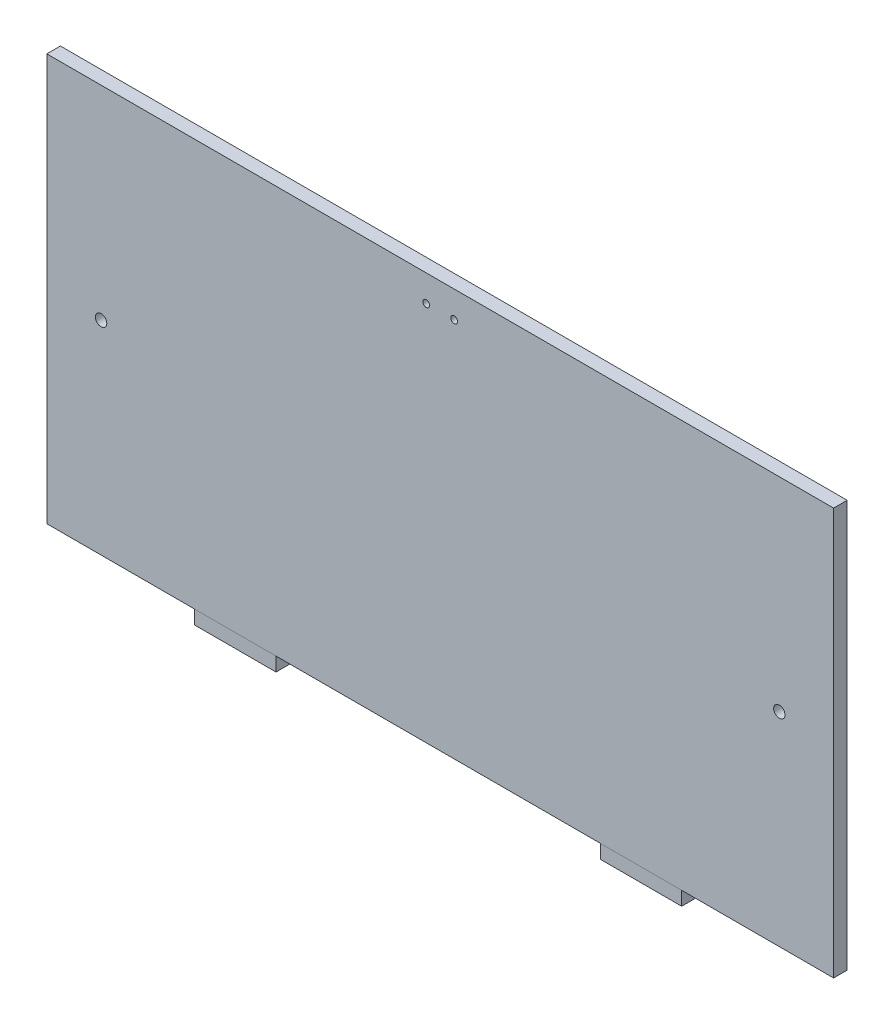
SolidWorks part; units mm, degrees
ref_plane "Front Plane" through (0, 0, 0) normal (0, 0, 1) x (1, 0, 0)
ref_plane "Top Plane" through (0, 0, 0) normal (0, 1, 0) x (1, 0, 0)
ref_plane "Right Plane" through (0, 0, 0) normal (1, 0, 0) x (0, 0, -1)
sketch "Sketch1" plane through (0, 0, 0) normal (0, 0, 1) x (1, 0, 0)
  line L1 (-145, 75) -> (145, 75)
  line L2 (-145, 75) -> (-145, -75)
  line L3 (-145, -75) -> (145, -75)
  line L4 (145, 75) -> (145, -75)
  line L5 (-145, 75) -> (145, -75) construction
  line L6 (-145, -75) -> (145, 75) construction
  point P0 (0, 0)
  dimension "D1" = 290
  dimension "D2" = 150
extrude "Boss-Extrude1" add sketch "Sketch1" along normal blind 5
sketch "Sketch2" plane through (0, 0, 5) normal (0, 0, 1) x (1, 0, 0)
  line L0 (-147.5, 65.2) -> (147.5, 65.2) construction
  line L3 (145, 75) -> (-145, 75) construction
  line L4 (0, 65.2) -> (-5.15, 65.2)
  line L5 (0, 65.2) -> (5.15, 65.2)
  circle A0 centre (-5.15, 65.2) radius 1.25
  circle A1 centre (5.15, 65.2) radius 1.25
  dimension "D2" = 5.15
  dimension "D3" = 2.5
  dimension "D4" = 2.5
  dimension "D1" = 9.8
  dimension "D5" = 5.15
extrude "Cut-Extrude1" cut sketch "Sketch2" against normal blind 5 contours A0 L0 L4 | L0 A0 L4 | L5 L0 A1 | L0 L5 A1
sketch "Sketch3" plane through (0, 0, 5) normal (0, 0, 1) x (1, 0, 0)
  line L0 (0, -75) -> (-145, -75)
  line L2 (-145, -75) -> (145, -75) construction
  line L3 (0, -75) -> (145, -75)
  line L4 (-90.52, -69.9) -> (-60.52, -69.9)
  line L5 (-90.52, -69.9) -> (-90.52, -80.1)
  line L6 (-90.52, -80.1) -> (-60.52, -80.1)
  line L7 (-60.52, -69.9) -> (-60.52, -80.1)
  line L8 (-90.52, -69.9) -> (-60.52, -80.1) construction
  line L9 (-90.52, -80.1) -> (-60.52, -69.9) construction
  line L10 (59, -69.9) -> (89, -69.9)
  line L11 (59, -69.9) -> (59, -80.1)
  line L12 (59, -80.1) -> (89, -80.1)
  line L13 (89, -69.9) -> (89, -80.1)
  line L14 (59, -69.9) -> (89, -80.1) construction
  line L15 (59, -80.1) -> (89, -69.9) construction
  point P5 (-75.52, -75)
  point P12 (74, -75)
  dimension "D1" = 30
  dimension "D2" = 30
  dimension "D3" = 10.2
  dimension "D4" = 10.2
  dimension "D5" = 74
  dimension "D6" = 75.52
extrude "Boss-Extrude2" add sketch "Sketch3" against normal blind 5 separate body contours L7 L0 L5 L6 | L13 L3 L11 L12
sketch "Sketch4" plane through (0, 0, 0) normal (0, 0, -1) x (-1, 0, 0)
  line L0 (-145, -75) -> (-145, 75) construction
  line L1 (-145, 75) -> (145, 75) construction
  line L2 (0, 75) -> (0, -75) construction
  line L3 (145, -75) -> (-145, -75) construction
  circle A0 centre (-125, 0) radius 2.1
  circle A1 centre (125, 0) radius 2.1
  dimension "D3" = 4.2
  dimension "D1" = 20
  dimension "D2" = 75
extrude "Cut-Extrude2" cut sketch "Sketch4" against normal blind 10
sketch "Sketch5" plane through (0, 0, 0) normal (0, 0, -1) x (-1, 0, 0)
  line L0 (145, 0) -> (60, 0) construction
  line L1 (145, 75) -> (145, -75) construction
  circle A0 centre (60, 0) radius 10.1
  dimension "D1" = 85
extrude "Cut-Extrude3" [suppressed] cut sketch "Sketch5" against normal blind 10
sketch "Sketch6" plane through (0, 0, 0) normal (0, 0, -1) x (-1, 0, 0)
  line L0 (-145, 0) -> (145, 0) construction
  line L1 (-145, -75) -> (-145, 75) construction
  line L2 (145, 75) -> (145, -75) construction
  circle A0 centre (-60, 29.5) radius 2.1
  circle A1 centre (-60, -29.5) radius 2.1
  dimension "D1" = 4.2
  dimension "D4" = 4.2
  dimension "D2" = 29.5
  dimension "D3" = 29.5
  dimension "D5" = 85
  dimension "D6" = 85
extrude "Cut-Extrude4" [suppressed] cut sketch "Sketch6" against normal blind 10
sketch "Sketch7" [suppressed] plane through (0, 0, 0) normal (0, 0, -1) x (-1, 0, 0)
  circle A0 centre (60, 0) radius 20 construction
  circle A1 centre (60, 20) radius 2.1
  circle A2 centre (80, 0) radius 2.1
  circle A3 centre (60, -20) radius 2.1
  circle A4 centre (40, 0) radius 2.1
  dimension "D1" = 40
  dimension "D2" = 4.2
  dimension "D3" = 4.2
  dimension "D4" = 4.2
  dimension "D5" = 4.2
extrude "Cut-Extrude5" [suppressed] cut sketch "Sketch7" against normal blind 10
sketch "Sketch8" [suppressed] plane through (0, 0, 0) normal (0, 0, -1) x (-1, 0, 0)
  line L0 (0, 0) -> (-29, 0) construction
  line L1 (-32.5, 10) -> (-25.5, 10)
  line L2 (-32.5, 10) -> (-32.5, -10)
  line L3 (-32.5, -10) -> (-25.5, -10)
  line L4 (-25.5, 10) -> (-25.5, -10)
  line L5 (-32.5, 10) -> (-25.5, -10) construction
  line L6 (-32.5, -10) -> (-25.5, 10) construction
  line L7 (60, 0) -> (-29, 0) construction
  point P0 (-29, 0)
  dimension "D1" = 7
  dimension "D2" = 20
  dimension "D3" = 89
extrude "Cut-Extrude6" [suppressed] cut sketch "Sketch8" against normal blind 10
